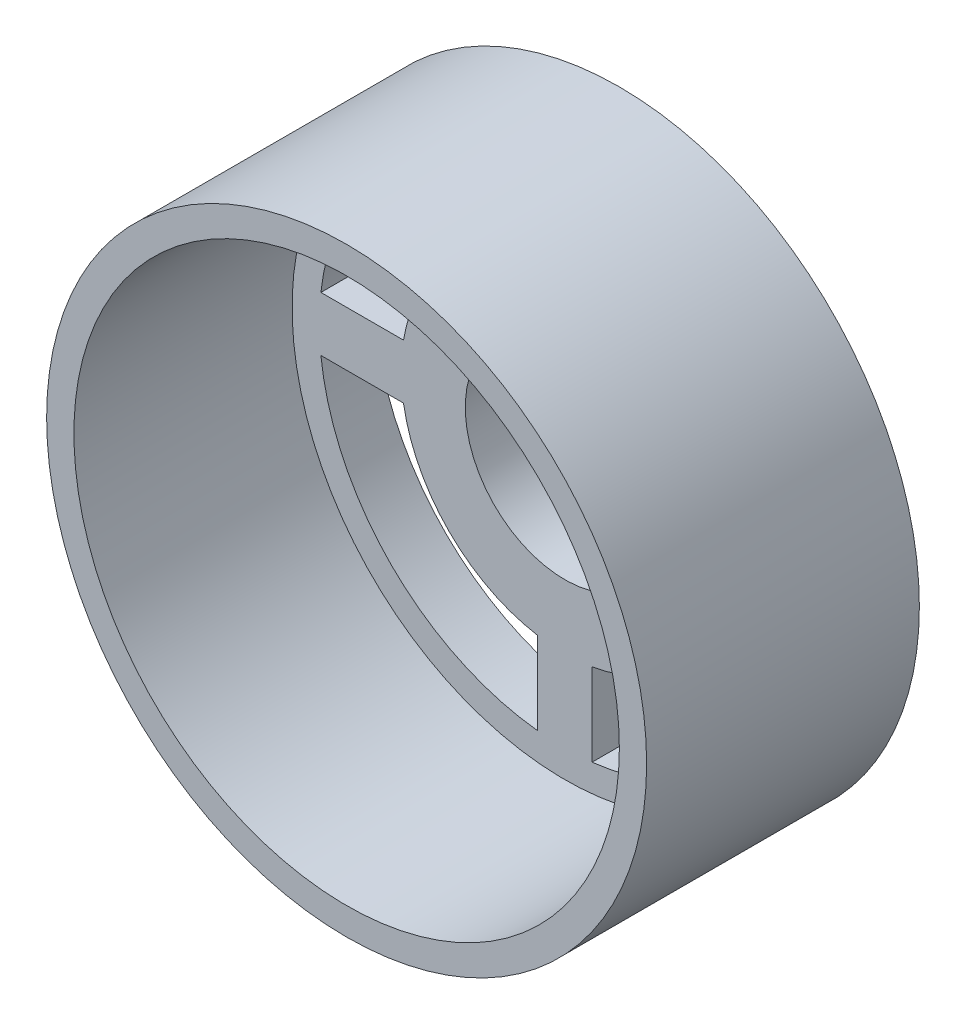
SolidWorks part; units mm, degrees
ref_plane "Plano frontal" through (0, 0, 0) normal (0, 0, 1) x (1, 0, 0)
ref_plane "Plano superior" through (0, 0, 0) normal (0, 1, 0) x (1, 0, 0)
ref_plane "Plano direito" through (0, 0, 0) normal (1, 0, 0) x (0, 0, -1)
sketch "Esboço1" plane through (0, 0, 0) normal (0, 0, 1) x (1, 0, 0)
  circle A0 centre (0, 0) radius 10
  circle A1 centre (0, 0) radius 3.65
  dimension "D1" = 20
  dimension "D2" = 7.3
extrude "Ressalto-extrusão1" add sketch "Esboço1" along normal blind 2
sketch "Esboço2" plane through (0, 0, 0) normal (0, 0, 1) x (1, 0, 0)
  circle A0 centre (0, 0) radius 11
  circle A2 centre (0, 0) radius 10
  dimension "D1" = 22
extrude "Ressalto-extrusão2" add sketch "Esboço2" along normal blind 10
sketch "Esboço3" plane through (0, 0, 0) normal (0, 0, -1) x (-1, 0, 0)
  line L1 (0, 0) -> (0, 5.4331) construction
  line L3 (-8.9443, -1) -> (-6, -1)
  line L4 (-8.9443, 1) -> (-6, 1)
  line L8 (1, 6) -> (1, 8.9443)
  line L9 (6, -1) -> (8.9443, -1)
  line L10 (-1, -6) -> (-1, -8.9443)
  line L11 (-1, 6) -> (-1, 8.9443)
  line L12 (6, 1) -> (8.9443, 1)
  line L13 (1, -6) -> (1, -8.9443)
  line L14 (-6, 1) -> (-5.9161, 1)
  line L15 (-6, -1) -> (-5.9161, -1)
  line L16 (-1, -6) -> (-1, -5.9161)
  line L17 (1, -6) -> (1, -5.9161)
  line L18 (6, -1) -> (5.9161, -1)
  line L19 (6, 1) -> (5.9161, 1)
  line L20 (1, 6) -> (1, 5.9161)
  line L21 (-1, 6) -> (-1, 5.9161)
  line L22 (-6, 0) -> (0, 0) construction
  arc A3 (-5.9161, -1) -> (-1, -5.9161) centre (0, 0) ccw
  arc A4 (-8.9443, -1) -> (-1, -8.9443) centre (0, 0) ccw
  arc A5 (-1, 5.9161) -> (-5.9161, 1) centre (0, 0) ccw
  arc A6 (-1, 8.9443) -> (-8.9443, 1) centre (0, 0) ccw
  arc A7 (8.9443, 1) -> (1, 8.9443) centre (0, 0) ccw
  arc A8 (5.9161, 1) -> (1, 5.9161) centre (0, 0) ccw
  arc A9 (1, -8.9443) -> (8.9443, -1) centre (0, 0) ccw
  arc A10 (1, -5.9161) -> (5.9161, -1) centre (0, 0) ccw
  dimension "D1" = 12
  dimension "D2" = 18
extrude "Corte-extrusão1" cut sketch "Esboço3" against normal blind 10
